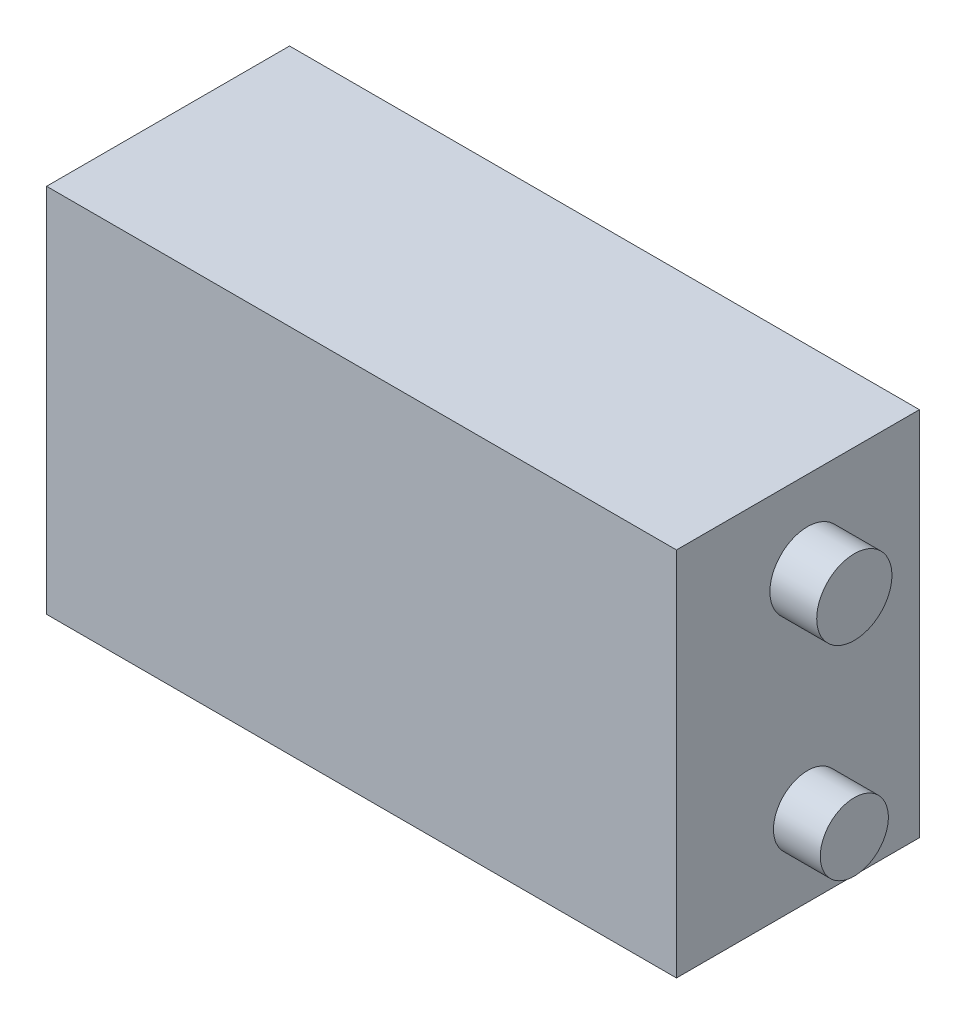
SolidWorks part; units mm, degrees
ref_plane "Front Plane" through (0, 0, 0) normal (0, 0, 1) x (1, 0, 0)
ref_plane "Top Plane" through (0, 0, 0) normal (0, 1, 0) x (1, 0, 0)
ref_plane "Right Plane" through (0, 0, 0) normal (1, 0, 0) x (0, 0, -1)
sketch "Sketch1" plane through (0, 0, 0) normal (0, 0, 1) x (1, 0, 0)
  line L1 (-22.225, -13.081) -> (22.225, -13.081)
  line L2 (-22.225, -13.081) -> (-22.225, 13.081)
  line L3 (-22.225, 13.081) -> (22.225, 13.081)
  line L4 (22.225, -13.081) -> (22.225, 13.081)
  line L5 (-22.225, -13.081) -> (22.225, 13.081) construction
  line L6 (-22.225, 13.081) -> (22.225, -13.081) construction
  point P0 (0, 0)
  dimension "D1" = 26.162
  dimension "D2" = 44.45
extrude "Boss-Extrude1" add sketch "Sketch1" along normal blind 17.145
sketch "Sketch2" plane through (22.225, 0, 0) normal (1, 0, 0) x (0, 0, -1)
  circle A0 centre (-7.8968, 7.227) radius 2.653
  circle A1 centre (-7.8968, -7.4288) radius 2.4014
extrude "Boss-Extrude2" add sketch "Sketch2" along normal blind 3.302
